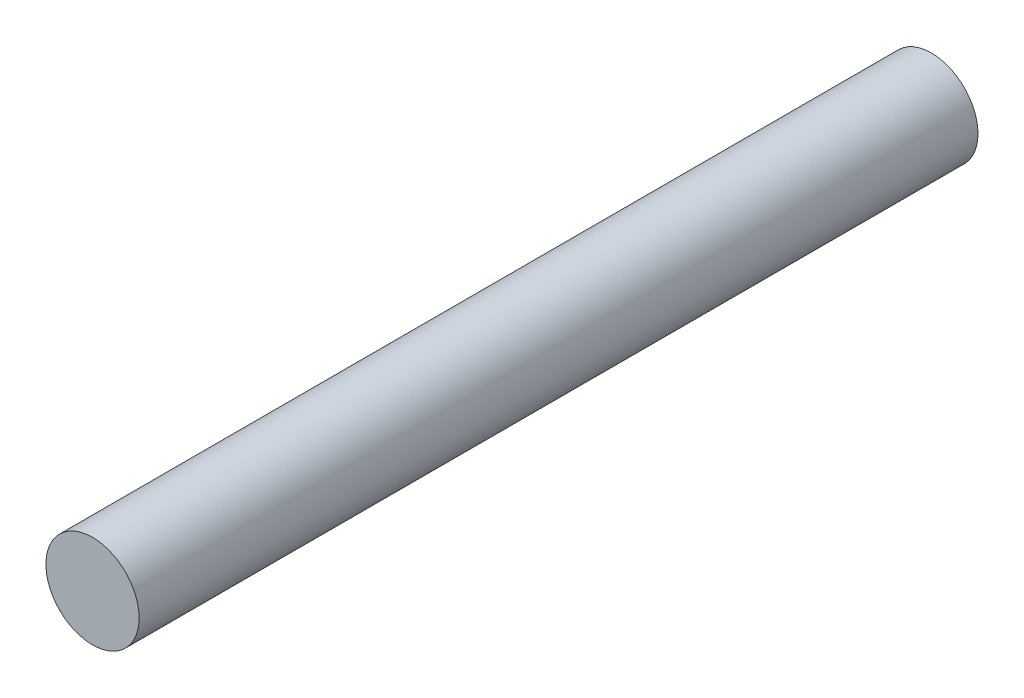
SolidWorks part; units mm, degrees
ref_plane "Front Plane" through (0, 0, 0) normal (0, 0, 1) x (1, 0, 0)
ref_plane "Top Plane" through (0, 0, 0) normal (0, 1, 0) x (1, 0, 0)
ref_plane "Right Plane" through (0, 0, 0) normal (1, 0, 0) x (0, 0, -1)
sketch "Sketch1" plane through (0, 0, 0) normal (0, 0, 1) x (1, 0, 0)
  circle A0 centre (0, 0) radius 3
  dimension "D1" = 6
extrude "Boss-Extrude1" add sketch "Sketch1" along normal blind 54 contours A0
